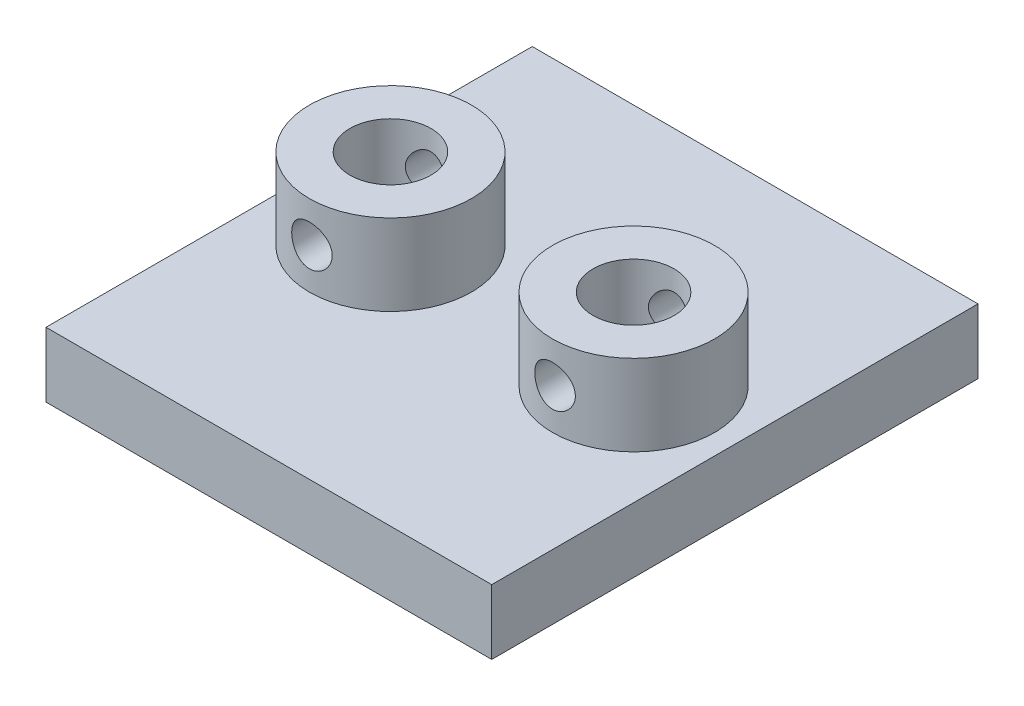
SolidWorks part; units mm, degrees
ref_plane "Front Plane" through (0, 0, 0) normal (0, 0, 1) x (1, 0, 0)
ref_plane "Top Plane" through (0, 0, 0) normal (0, 1, 0) x (1, 0, 0)
ref_plane "Right Plane" through (0, 0, 0) normal (1, 0, 0) x (0, 0, -1)
sketch "Sketch1" plane through (0, 0, 0) normal (0, 1, 0) x (1, 0, 0)
  line L1 (-5.5, 6) -> (5.5, 6)
  line L2 (-5.5, 6) -> (-5.5, -6)
  line L3 (-5.5, -6) -> (5.5, -6)
  line L4 (5.5, 6) -> (5.5, -6)
  line L5 (-5.5, 6) -> (5.5, -6) construction
  line L6 (-5.5, -6) -> (5.5, 6) construction
  point P0 (0, 0)
  dimension "D1" = 12
  dimension "D2" = 11
extrude "Boss-Extrude1" add sketch "Sketch1" along normal blind 1.6
sketch "Sketch2" plane through (0, 1.6, 0) normal (0, 1, 0) x (1, 0, 0)
  line L0 (-3, 0) -> (3, 0) construction
  circle A0 centre (-3, 0) radius 2
  circle A1 centre (3, 0) radius 2
  circle A7 centre (-3, 0) radius 1
  circle A8 centre (3, 0) radius 1
  circle A12 centre (9, 0) radius 2 [skipped]
  point P2 (0, 0)
  dimension "D1" = 4
  dimension "D3" = 6
  dimension "D2" = 3
extrude "Boss-Extrude2" add sketch "Sketch2" along normal blind 2
sketch "Sketch3" plane through (0, 0, 0) normal (0, 0, 1) x (1, 0, 0)
  line L0 (-3, 3.6) -> (-3, 2.6) construction
  line L1 (-1, 3.6) -> (-5, 3.6) construction
  circle A0 centre (-3, 2.6) radius 0.5
  circle A1 centre (3, 2.6) radius 0.5
  dimension "D1" = 1
  dimension "D2" = 1
extrude "Cut-Extrude1" cut sketch "Sketch3" against normal blind 2 and the other way blind 2
